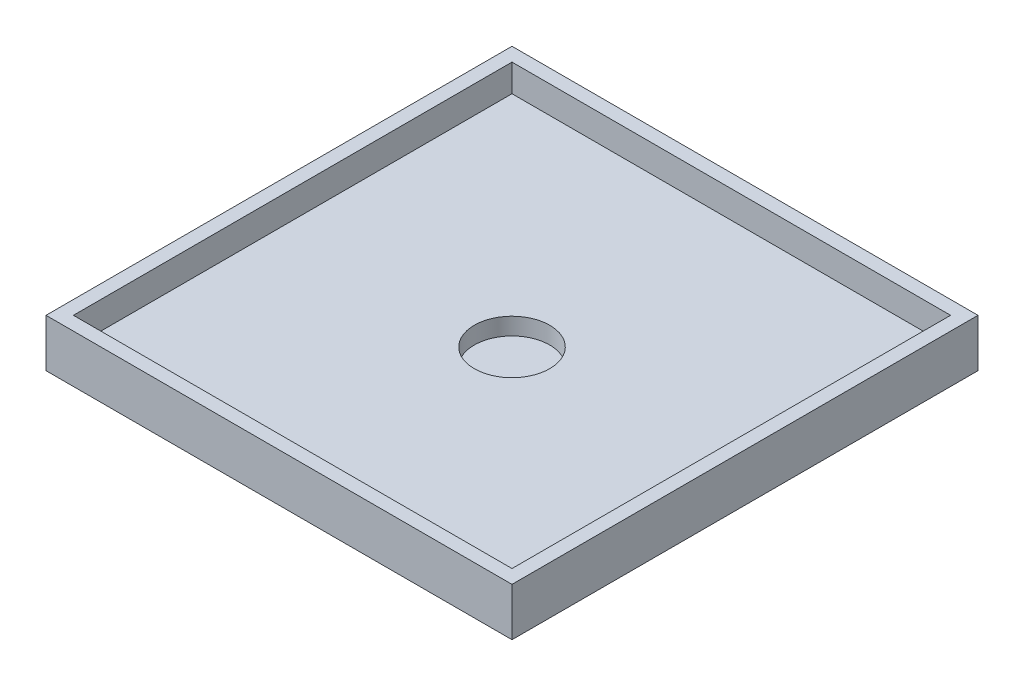
SolidWorks part; units mm, degrees
ref_plane "Front Plane" through (0, 0, 0) normal (0, 0, 1) x (1, 0, 0)
ref_plane "Top Plane" through (0, 0, 0) normal (0, 1, 0) x (1, 0, 0)
ref_plane "Right Plane" through (0, 0, 0) normal (1, 0, 0) x (0, 0, -1)
sketch "Sketch1" plane through (0, 0, 0) normal (0, 1, 0) x (1, 0, 0)
  line L1 (-34, -34) -> (34, -34)
  line L2 (-34, -34) -> (-34, 34)
  line L3 (-34, 34) -> (34, 34)
  line L4 (34, -34) -> (34, 34)
  line L5 (-34, -34) -> (34, 34) construction
  line L6 (-34, 34) -> (34, -34) construction
  point P0 (0, 0)
  dimension "D1" = 68
  dimension "D2" = 68
extrude "Boss-Extrude1" add sketch "Sketch1" along normal blind 7
sketch "Sketch2" plane through (0, 7, 0) normal (0, 1, 0) x (1, 0, 0)
  line L1 (-32, -32) -> (32, -32)
  line L2 (-32, -32) -> (-32, 32)
  line L3 (-32, 32) -> (32, 32)
  line L4 (32, -32) -> (32, 32)
  line L5 (-32, -32) -> (32, 32) construction
  line L6 (-32, 32) -> (32, -32) construction
  point P0 (0, 0)
  dimension "D1" = 64
  dimension "D2" = 64
extrude "Cut-Extrude1" cut sketch "Sketch2" against normal blind 4
sketch "Sketch3" plane through (0, 3, 0) normal (0, 1, 0) x (1, 0, 0)
  circle A0 centre (0, 0) radius 5.5
  dimension "D1" = 11
extrude "Cut-Extrude2" cut sketch "Sketch3" against normal blind 2.5
